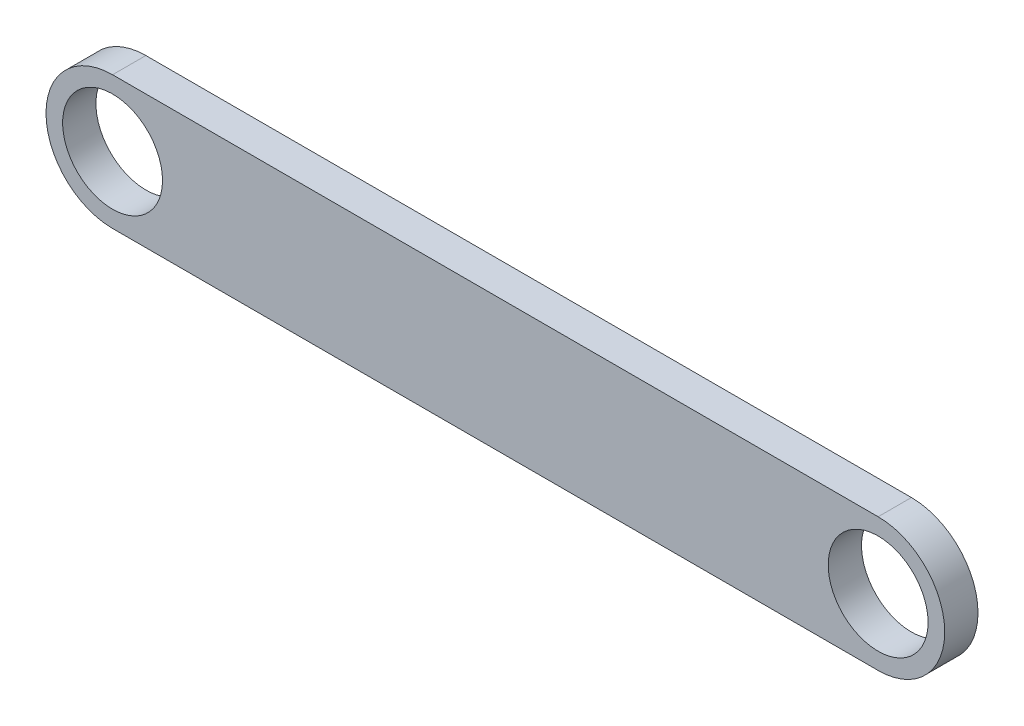
SolidWorks part; units mm, degrees
ref_plane "Спереди" through (0, 0, 0) normal (0, 0, 1) x (1, 0, 0)
ref_plane "Сверху" through (0, 0, 0) normal (0, 1, 0) x (1, 0, 0)
ref_plane "Справа" through (0, 0, 0) normal (1, 0, 0) x (0, 0, -1)
other "Configuration Table"
sketch "Эскиз1" plane through (0, 0, 0) normal (0, 0, 1) x (1, 0, 0)
  line L0 (0, 0) -> (230, 0) construction
  line L1 (0, 20) -> (230, 20)
  line L2 (0, -20) -> (230, -20)
  arc A0 (0, 20) -> (0, -20) centre (0, 0) ccw
  arc A1 (230, -20) -> (230, 20) centre (230, 0) ccw
  circle A2 centre (0, 0) radius 15
  circle A3 centre (230, 0) radius 15
  point P3 (115, 0)
  dimension "D3" = 30
  dimension "D4" = 30
  dimension "D1" = 230
  dimension "D2" = 40
extrude "Бобышка-Вытянуть1" add sketch "Эскиз1" along normal blind 10
